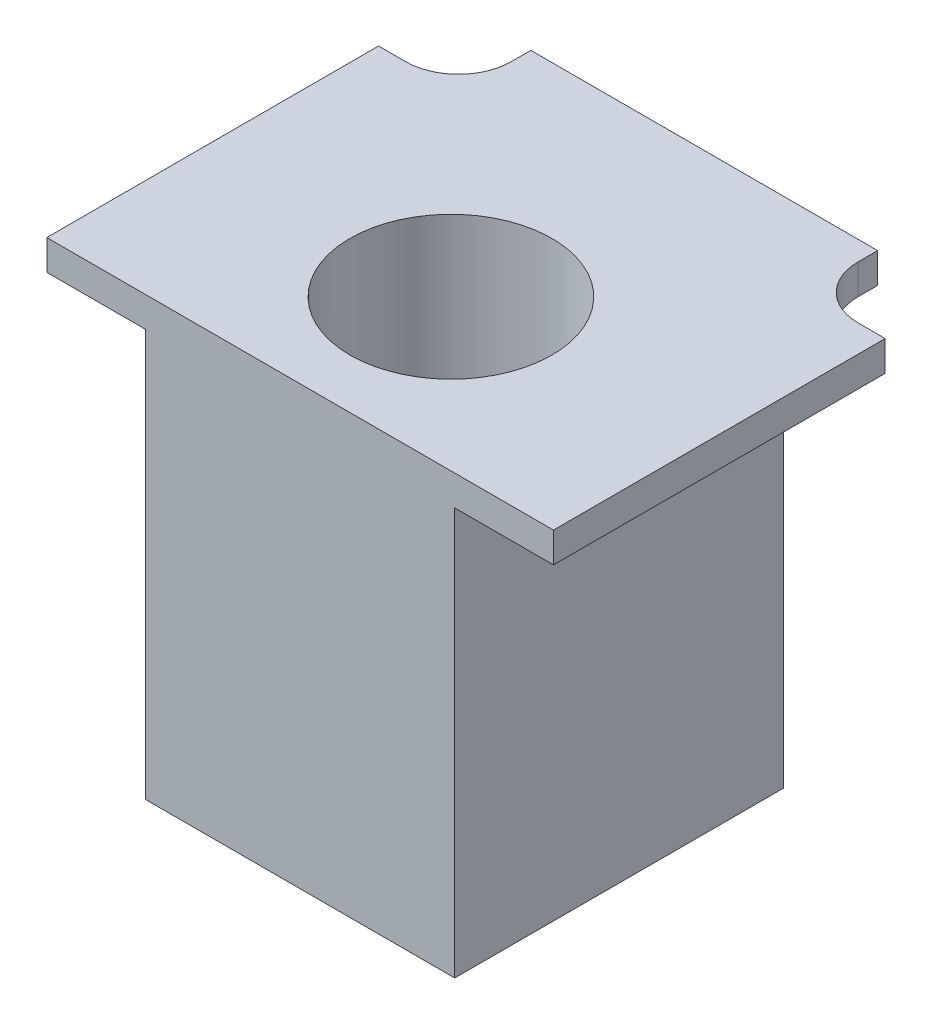
SolidWorks part; units mm, degrees
ref_plane "Front Plane" through (0, 0, 0) normal (0, 0, 1) x (1, 0, 0)
ref_plane "Top Plane" through (0, 0, 0) normal (0, 1, 0) x (1, 0, 0)
ref_plane "Right Plane" through (0, 0, 0) normal (1, 0, 0) x (0, 0, -1)
sketch "Sketch1" plane through (0, 0, 0) normal (0, 1, 0) x (1, 0, 0)
  line L1 (-5.125, 5.45) -> (5.125, 5.45)
  line L2 (-5.125, 5.45) -> (-5.125, -5.45)
  line L3 (-5.125, -5.45) -> (5.125, -5.45)
  line L4 (5.125, 5.45) -> (5.125, -5.45)
  line L5 (-5.125, 5.45) -> (5.125, -5.45) construction
  line L6 (-5.125, -5.45) -> (5.125, 5.45) construction
  point P0 (0, 0)
  dimension "D1" = 10.9
  dimension "D2" = 10.25
extrude "Boss-Extrude1" add sketch "Sketch1" along normal blind 1.5
sketch "Sketch2" plane through (0, 1.5, 0) normal (0, 1, 0) x (1, 0, 0)
  line L0 (-5.125, -5.45) -> (5.125, -5.45) construction
  line L5 (5.125, 5.45) -> (-5.125, 5.45) construction
  line L6 (-3.195, 3.75) -> (3.195, 3.75)
  line L7 (5.125, -5.45) -> (5.125, 5.45) construction
  line L8 (-5.125, 5.45) -> (-5.125, -5.45) construction
  line L11 (-3.195, 3.75) -> (-3.195, -4.65)
  line L12 (-3.195, -4.65) -> (3.195, -4.65)
  line L13 (3.195, 3.75) -> (3.195, -4.65)
  dimension "D1" = 1.7
  dimension "D2" = 0.8
  dimension "D3" = 1.93
  dimension "D4" = 1.93
extrude "Cut-Extrude1" cut sketch "Sketch2" against normal through all
sketch "Sketch3" plane through (0, 1.5, 0) normal (0, 1, 0) x (1, 0, 0)
  line L1 (-5.125, 5.45) -> (5.125, 5.45)
  line L2 (-5.125, 5.45) -> (-5.125, -5.45)
  line L3 (-5.125, -5.45) -> (5.125, -5.45)
  line L4 (5.125, 5.45) -> (5.125, -5.45)
  circle A0 centre (0, -0.45) radius 3.35
  dimension "D1" = 6.7
  dimension "D2" = 5.9
extrude "Boss-Extrude2" add sketch "Sketch3" along normal blind 13
sketch "Sketch5" plane through (0, 14.5, 0) normal (0, 1, 0) x (1, 0, 0)
  line L5 (-5.125, -5.45) -> (5.125, -5.45) construction
  line L44 (-10, 9.55) -> (10, 9.55) construction
  line L49 (-10, 9.55) -> (-10, -5.45) construction
  line L50 (-10, -5.45) -> (10, -5.45) construction
  line L51 (10, 9.55) -> (10, -5.45) construction
  line L53 (0, -0.45) -> (-4, -0.45) construction
  line L54 (-9.12, 8.67) -> (9.12, 8.67) construction
  line L55 (-9.12, 8.67) -> (-9.12, -5.45) construction
  line L56 (-9.12, -5.45) -> (9.12, -5.45) construction
  line L57 (9.12, 8.67) -> (9.12, -5.45) construction
  line L58 (-8.4, 7.95) -> (8.4, 7.95) construction
  line L59 (-8.4, 7.95) -> (-8.4, -5.45) construction
  line L60 (-8.4, -5.45) -> (8.4, -5.45) construction
  line L61 (8.4, 7.95) -> (8.4, -5.45) construction
  line L62 (0, -0.45) -> (0, -4.45) construction
  line L63 (-5.75, 7.3) -> (-5.75, 7.95)
  line L64 (-7.5, 5.55) -> (-8.4, 5.55)
  line L65 (-8.4, 7.95) -> (-5.75, 7.95)
  line L66 (-8.4, 5.55) -> (-8.4, 7.95)
  line L67 (7.5, 5.55) -> (8.4, 5.55)
  line L68 (8.4, 5.55) -> (8.4, 7.95)
  line L69 (5.75, 7.3) -> (5.75, 7.95)
  line L70 (5.75, 7.95) -> (8.4, 7.95)
  line L71 (-8.4, 5.55) -> (-8.4, -5.45)
  line L72 (-8.4, -5.45) -> (8.4, -5.45)
  line L73 (8.4, -5.45) -> (8.4, 5.55)
  line L74 (-5.75, 7.95) -> (5.75, 7.95)
  circle A0 centre (-7.5, 7.3) radius 1.75 construction
  circle A1 centre (7.5, 7.3) radius 1.75 construction
  arc A4 (5.75, 7.3) -> (7.5, 5.55) centre (7.5, 7.3) ccw
  arc A5 (-7.5, 5.55) -> (-5.75, 7.3) centre (-7.5, 7.3) ccw
  point P10 (0, -0.45)
  dimension "D4" = 0.88
  dimension "D10" = 3.5
  dimension "D3" = 10
  dimension "D5" = 0.88
  dimension "D7" = 1.6
  dimension "D8" = 1.6
  dimension "D13" = 10
  dimension "D2" = 10
  dimension "D6" = 0.88
  dimension "D9" = 1.6
  dimension "D11" = 2.25
  dimension "D12" = 2.5
extrude "Boss-Extrude3" add sketch "Sketch5" against normal blind 1
